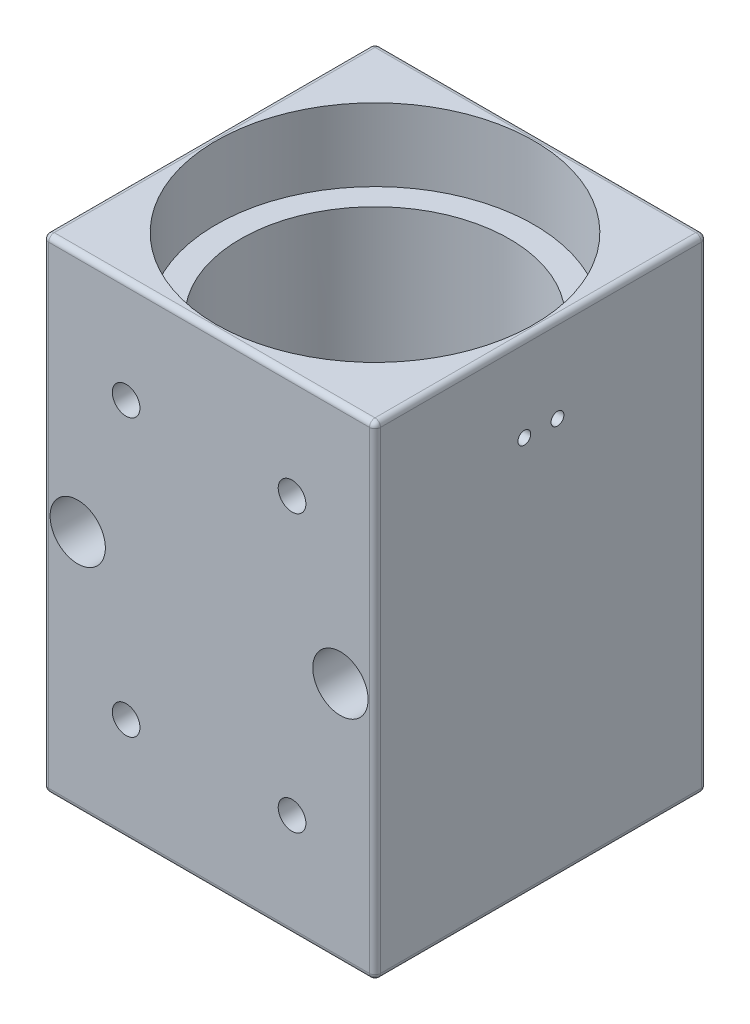
SolidWorks part; units mm, degrees
material "AISI 4130 Steel, normalized at 870C"
ref_plane "Front Plane" through (0, 0, 0) normal (0, 0, 1) x (1, 0, 0)
ref_plane "Top Plane" through (0, 0, 0) normal (0, 1, 0) x (1, 0, 0)
ref_plane "Right Plane" through (0, 0, 0) normal (1, 0, 0) x (0, 0, -1)
sketch "Sketch1" plane through (0, 0, 0) normal (0, 0, 1) x (1, 0, 0)
  line L1 (-38.1, -55.5625) -> (38.1, -55.5625)
  line L2 (-38.1, -55.5625) -> (-38.1, 55.5625)
  line L3 (-38.1, 55.5625) -> (38.1, 55.5625)
  line L4 (38.1, -55.5625) -> (38.1, 55.5625)
  line L5 (-38.1, -55.5625) -> (38.1, 55.5625) construction
  line L6 (-38.1, 55.5625) -> (38.1, -55.5625) construction
  point P0 (0, 0)
  dimension "D1" = 111.125
  dimension "D2" = 76.2
extrude "Boss-Extrude1" add sketch "Sketch1" along normal blind 76.2
sketch "Sketch2" plane through (0, 55.5625, 0) normal (0, 1, 0) x (1, 0, 0)
  line L0 (-38.1, 0) -> (38.1, -76.2) construction
  line L1 (38.1, 0) -> (-38.1, 0) construction
  circle A0 centre (0, -38.1) radius 30.861
  dimension "D1" = 61.722
extrude "Cut-Extrude1" cut sketch "Sketch2" against normal blind 127
sketch "Sketch3" plane through (0, 55.5625, 0) normal (0, 1, 0) x (1, 0, 0)
  circle A0 centre (0, -38.1) radius 36.5125
  dimension "D1" = 73.025
extrude "Cut-Extrude2" cut sketch "Sketch3" against normal blind 16.6687
sketch "Sketch4" plane through (0, -55.5625, 0) normal (0, -1, 0) x (1, 0, 0)
  circle A0 centre (0, 38.1) radius 36.5125
  dimension "D1" = 73.025
extrude "Cut-Extrude3" cut sketch "Sketch4" against normal blind 16.6687
sketch "Sketch5" plane through (0, 0, 76.2) normal (0, 0, 1) x (1, 0, 0)
  line L0 (-38.1, 55.5625) -> (-38.1, -55.5625) construction
  line L1 (38.1, 55.5625) -> (38.1, -55.5625) construction
  line L2 (-22.225, 55.5625) -> (-22.225, -55.5625) construction
  line L3 (38.1, 55.5625) -> (-38.1, 55.5625) construction
  line L4 (-38.1, -55.5625) -> (38.1, -55.5625) construction
  line L5 (22.225, 55.5625) -> (22.225, -55.5625) construction
  line L6 (-22.225, 0) -> (22.225, 0) construction
  line L7 (-38.1, 0) -> (-22.225, 0) construction
  line L8 (22.225, 0) -> (38.1, 0) construction
  circle A0 centre (-30.1625, 0) radius 6.35
  circle A1 centre (30.1625, 0) radius 6.35
  dimension "D2" = 12.7
  dimension "D3" = 12.7
  dimension "D1" = 44.45
extrude "Cut-Extrude4" cut sketch "Sketch5" against normal through all
sketch "Sketch6" plane through (0, 0, 76.2) normal (0, 0, 1) x (1, 0, 0)
  line L0 (-23.8125, 0) -> (23.8125, 0) construction
  line L2 (38.1, 55.5625) -> (-38.1, 55.5625) construction
  line L3 (0, 55.5625) -> (0, -55.5625) construction
  line L4 (-38.1, -55.5625) -> (38.1, -55.5625) construction
  line L5 (19.05, -31.75) -> (-19.05, -31.75)
  line L6 (19.05, -31.75) -> (19.05, 31.75)
  line L7 (19.05, 31.75) -> (-19.05, 31.75)
  line L8 (-19.05, -31.75) -> (-19.05, 31.75)
  line L9 (19.05, -31.75) -> (-19.05, 31.75) construction
  line L10 (19.05, 31.75) -> (-19.05, -31.75) construction
  circle A0 centre (-30.1625, 0) radius 6.35 construction
  circle A1 centre (30.1625, 0) radius 6.35 construction
  circle A2 centre (-19.05, 31.75) radius 3.175
  circle A3 centre (19.05, 31.75) radius 3.175
  circle A4 centre (-19.05, -31.75) radius 3.175
  circle A5 centre (19.05, -31.75) radius 3.175
  point P7 (0, 0)
  dimension "D3" = 6.35
  dimension "D4" = 6.35
  dimension "D5" = 6.35
  dimension "D6" = 6.35
  dimension "D1" = 38.1
  dimension "D2" = 63.5
extrude "Cut-Extrude5" cut sketch "Sketch6" against normal blind 12.7 contours L7 A2 L8 | L8 A2 L7 | L6 A3 L7 | L7 A3 L6 | L8 A4 L5 | L5 A4 L8 | L5 A5 L6 | L6 A5 L5
fillet "Fillet1" radius 1.27 12 edges at (-38.1, 0, 0) (38.1, 0, 0) (38.1, 55.5625, 38.1) (0, 55.5625, 0) (-38.1, 55.5625, 38.1) (0, 55.5625, 76.2) (38.1, 0, 76.2) (38.1, -55.5625, 38.1) (0, -55.5625, 0) (0, -55.5625, 76.2) (-38.1, 0, 76.2) (-38.1, -55.5625, 38.1)
sketch "Sketch7" plane through (0, 0, 0) normal (0, 0, -1) x (-1, 0, 0)
  circle A0 centre (-4.7625, 3.175) radius 1.8987
  circle A1 centre (-4.7625, -3.175) radius 1.8987
sketch "Sketch8" plane through (38.1, 0, 0) normal (-1, 0, 0) x (0, 0, 1)
  line L0 (68.961, 38.8938) -> (7.239, 38.8938) construction
  line L1 (68.961, 38.8938) -> (7.239, 38.8938)
  line L2 (38.1, 38.8938) -> (38.1, 35.7188) construction
  line L3 (30.48, 35.7188) -> (38.1, 35.7188) construction
  line L4 (30.48, 29.3688) -> (45.72, 29.3688)
  line L5 (30.48, 29.3688) -> (30.48, 42.0688)
  line L6 (30.48, 42.0688) -> (45.72, 42.0688)
  line L7 (45.72, 29.3688) -> (45.72, 42.0688)
  line L8 (30.48, 29.3688) -> (45.72, 42.0688) construction
  line L9 (30.48, 42.0688) -> (45.72, 29.3688) construction
  line L10 (38.1, 35.7188) -> (45.72, 35.7188) construction
  circle A0 centre (41.91, 35.7188) radius 1.4732
  circle A1 centre (34.29, 35.7188) radius 1.4732
  dimension "D4" = 2.9464
  dimension "D5" = 2.9464
  dimension "D1" = 3.175
  dimension "D2" = 12.7
  dimension "D3" = 7.62
extrude "Cut-Extrude6" cut sketch "Sketch8" along normal blind 23.622 contours A1 | A0
